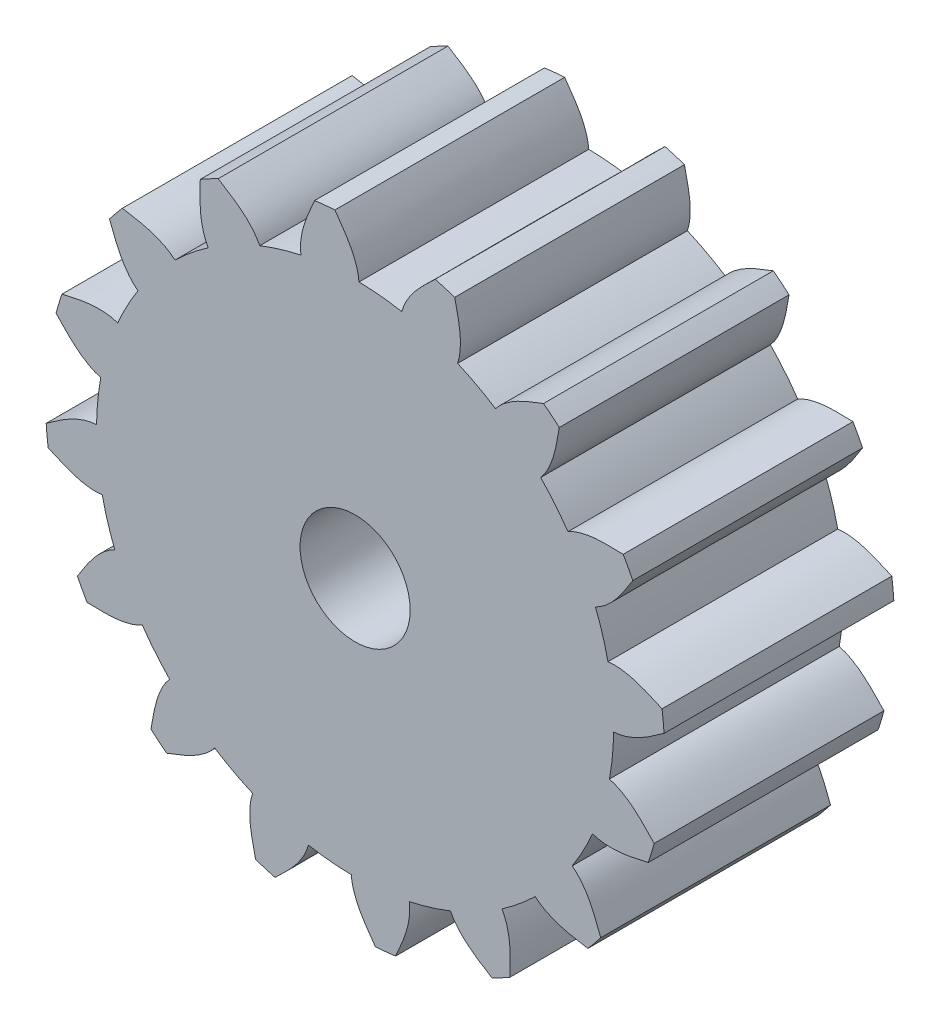
SolidWorks part; units mm, degrees
ref_plane "Front Plane" through (0, 0, 0) normal (0, 0, 1) x (1, 0, 0)
ref_plane "Top Plane" through (0, 0, 0) normal (0, 1, 0) x (1, 0, 0)
ref_plane "Right Plane" through (0, 0, 0) normal (1, 0, 0) x (0, 0, -1)
sketch "punti involuta" plane through (0, 0, 0) normal (0, 0, 1) x (1, 0, 0)
  line L0 (0, 0) -> (0, 4.6277) construction
  line L1 (-3.4916, 2) -> (3.4916, 2) construction
  line L2 (-3.4916, 0.7292) -> (3.4916, 3.2708) construction
  line L3 (0, 0) -> (-0.6428, 1.766) construction
  line L4 (-0.6428, 1.766) -> (0, 2) construction
  line L5 (-1.2414, 1.411) -> (-0.2023, 2.3252) construction
  line L6 (-0.3539, 1.8458) -> (0.0233, 1.9181) construction
  circle A0 centre (0, 0) radius 2 construction
  circle A1 centre (0, 0) radius 1.8794 construction
  arc A2 (-0.6428, 1.766) -> (-1.2414, 1.411) centre (0, 0) ccw construction
  arc A3 (-0.6428, 1.766) -> (-0.3539, 1.8458) centre (0, 0) cw construction
  arc A4 (-0.6428, 1.766) -> (0.028, 1.8792) centre (0, 0) cw construction
  point P4 (0, 2)
  point P7 (0, 2)
  dimension "D1" = 4
  dimension "D2" = 20
  dimension "D3" = 0.684
  dimension "D5" = 1.384
  dimension "D7" = 0.384
  dimension "D4" = 0.7
  dimension "D6" = 0.3
  dimension "D8" = 0.684
sketch "diametro testa" plane through (0, 0, 0) normal (0, 0, 1) x (1, 0, 0)
  circle A0 centre (0, 0) radius 2.25
  dimension "D1" = 4.5
sketch "profilo" plane through (0, 0, 0) normal (0, 0, 1) x (1, 0, 0)
  line L0 (0, 0) -> (-0.1842, 1.8703) construction
  line L1 (0, 0) -> (0, 4.6277) construction
  line L2 (-0.1842, 1.8703) -> (-0.2205, 2.2392)
  arc A1 (-0.2205, 2.2392) -> (-0.1467, 2.2452) centre (0, 0) cw
  circle A3 centre (0, 0) radius 2.25 construction
  arc A4 (0.028, 1.8792) -> (-0.1842, 1.8703) centre (0, 0) ccw
  arc A5 (0.028, 1.8792) -> (-0.6428, 1.766) centre (0, 0) ccw construction
  circle A6 centre (0, 0) radius 1.8794 construction
  spline S0 degree 3 poles (-0.2023, 2.3252) (-0.1183, 2.1969) (0.0168, 2.0487) (0.028, 1.8792) knots 0 0 0 0 1 1 1 1
  dimension "D1" = 5.625
sketch "diametro base" plane through (0, 0, 0) normal (0, 0, 1) x (1, 0, 0)
  circle A0 centre (0, 0) radius 1.8794
extrude "Boss-Extrude7" add sketch "profilo" along normal blind 1.67 contours S0 A1 L2 A4
ref_plane "Plane1" through (0, 0, 0) normal (0.9952, 0.098, 0) x (-0.098, 0.9952, 0)
mirror "Mirror1" about plane through (0, 0, 0) normal (0.9952, 0.098, 0) of bodies 112
pattern_circular "CirPattern1" count 16 over 360 about axis through (0, 0, 1.67) along (0, 0, 1) of bodies 113
extrude "Boss-Extrude9" add sketch "diametro base" along normal up to surface (1.67 mm away)
sketch "mozzo" plane through (0, 0, 0) normal (0, 0, 1) x (1, 0, 0)
  circle A0 centre (0, 0) radius 0.4
  dimension "D1" = 0.8
extrude "Cut-Extrude1" cut sketch "mozzo" along normal up to surface (1.67 mm away) up to face at (0, 0, 1.67)
equation "\"n_imposto\"= 16"
equation "\"m\"= .25"
equation "\"d_imposto\"= \"n_imposto\" * \"m\""
equation "\"alpha\"= 20"
equation "\"a1\"= .7"
equation "\"a2\"= .3"
equation "\"s\"= 1.67"
equation "\"D1@punti involuta\"=\"d_imposto\""
equation "\"D2@punti involuta\" = \"alpha\""
equation "\"D4@punti involuta\" = \"a1\""
equation "\"D5@punti involuta\" = \"D3@punti involuta\" + \"a1\""
equation "\"D6@punti involuta\" = \"a2\""
equation "\"D7@punti involuta\" = \"D3@punti involuta\" - \"a2\""
equation "\"D1@diametro testa\"=\"d_imposto\" + \"m\" * 2"
equation "\"D8@punti involuta\"=\"D3@punti involuta\""
equation "\"D1@profilo\"=360 / \"n_imposto\" / 4"
equation "\"D1@Boss-Extrude7\"=\"s\""
equation "\"D1@CirPattern1\"= \"n_imposto\""
equation "\"d_mozzo\"= .8"
equation "\"D1@mozzo\"=\"d_mozzo\""
